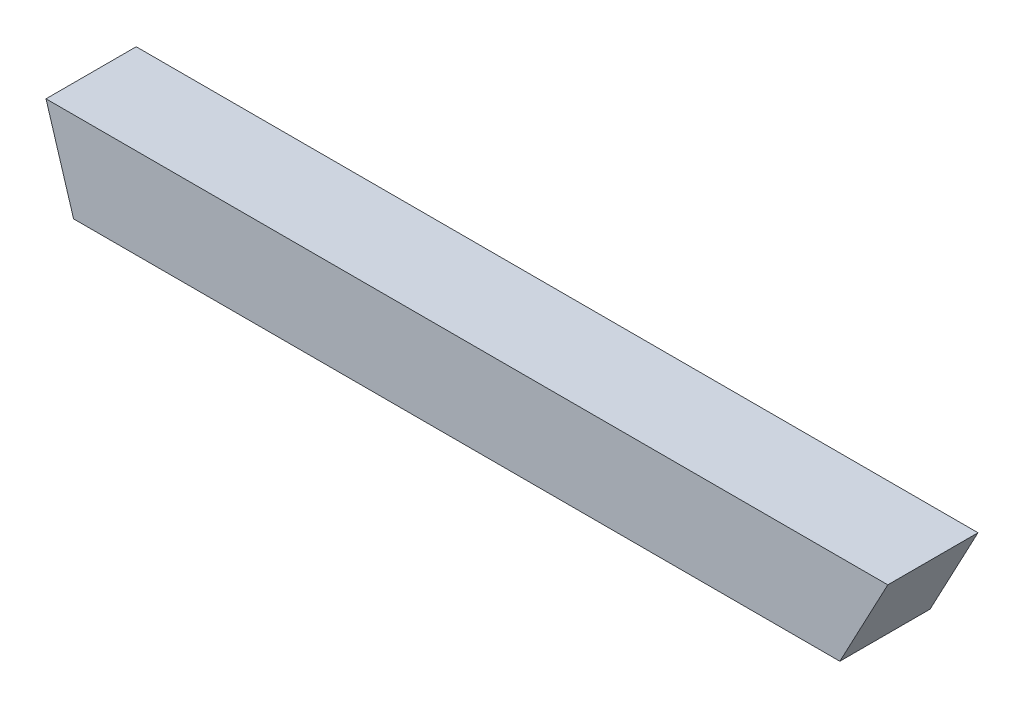
SolidWorks part; units mm, degrees
ref_plane "Front Plane" through (0, 0, 0) normal (0, 0, 1) x (1, 0, 0)
ref_plane "Top Plane" through (0, 0, 0) normal (0, 1, 0) x (1, 0, 0)
ref_plane "Right Plane" through (0, 0, 0) normal (1, 0, 0) x (0, 0, -1)
sketch "Sketch1" plane through (0, 0, 0) normal (0, 0, 1) x (1, 0, 0)
  line L0 (-46.0076, 0) -> (115.8392, 0)
  line L1 (115.8392, 0) -> (125.9682, 19.05)
  line L2 (125.9682, 19.05) -> (-51.8318, 19.05)
  line L3 (-51.8318, 19.05) -> (-46.0076, 0)
  line L4 (120.9037, 9.525) -> (-48.9197, 9.525)
  point P7 (0, 0)
  dimension "D1" = 62
  dimension "D2" = 73
  dimension "D3" = 19.05
  dimension "D4" = 9.525
  dimension "D5" = 177.8
extrude "Boss-Extrude2" add sketch "Sketch1" along normal blind 19.05 contours L4 L1 L2 L3 | L1 L4 L3 L0
